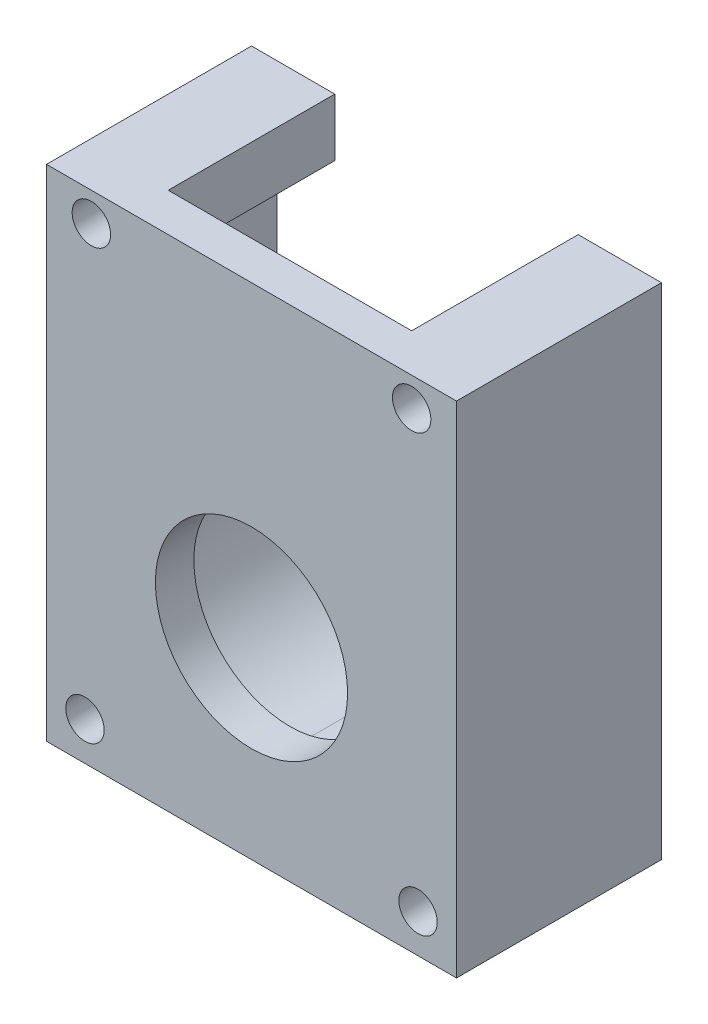
SolidWorks part; units mm, degrees
material "6063-O"
ref_plane "Front" through (0, 0, 0) normal (0, 0, 1) x (1, 0, 0)
ref_plane "Top" through (0, 0, 0) normal (0, 1, 0) x (1, 0, 0)
ref_plane "Right" through (0, 0, 0) normal (1, 0, 0) x (0, 0, -1)
sketch "Sketch1" plane through (0, 0, 0) normal (0, 0, 1) x (1, 0, 0)
  line L0 (-16, 0) -> (-16, 24)
  line L1 (-16, 24) -> (16, 24)
  line L2 (16, 24) -> (16, 0)
  line L3 (-14, 0) -> (-14, 24)
  line L4 (14, 0) -> (14, 24)
  line L5 (-16, 0) -> (-16, -15)
  line L6 (-16, -15) -> (16, -15)
  line L7 (16, -15) -> (16, 0)
  line L8 (14, -13) -> (14, 0)
  line L9 (14, 22) -> (14, 0)
  line L10 (-14, 22) -> (14, 22)
  line L11 (-14, 0) -> (-14, 22)
  line L12 (-14, 0) -> (-14, -13)
  line L13 (-14, -13) -> (14, -13)
  circle A0 centre (0, 0) radius 12.7
  circle A1 centre (0, 0) radius 14
  circle A2 centre (0, 0) radius 16
  dimension "D1" = 25.4
  dimension "D2" = 28
  dimension "D3" = 32
  dimension "D4" = 24
  dimension "D6" = 13
  dimension "D5" = 2
extrude "Boss-Extrude1" add sketch "Sketch1" along normal blind 19 contours A2 L11 L3 L1 L0 | L3 A2 L12 | A2 L5 L6 L13 L12 | L13 A2 L6 A1 | L13 A1 | A2 L6 L7 L8 L13 | A2 L4 L8 | A2 L2 L1 L4 L9
sketch "Sketch2" plane through (0, 0, 19) normal (0, 0, 1) x (1, 0, 0)
  line L1 (-14, 24) -> (-9.5, 24)
  line L2 (-14, 24) -> (-14, 19.5)
  line L3 (-14, 19.5) -> (-9.5, 19.5)
  line L4 (-9.5, 24) -> (-9.5, 19.5)
  line L7 (14, 24) -> (9.5, 24)
  line L8 (14, 24) -> (14, 19.5)
  line L9 (14, 19.5) -> (9.5, 19.5)
  line L10 (9.5, 24) -> (9.5, 19.5)
  dimension "D1" = 4.5
  dimension "4.5" = 4.5
extrude "Boss-Extrude2" add sketch "Sketch2" against normal blind 19
fillet "Fillet1" radius 10 1 edges at (-14, -13, 9.5)
fillet "Fillet2" radius 10 1 edges at (14, -13, 9.5)
fillet "Fillet3" radius 1 2 edges at (-14, 19.5, 9.5) (14, 19.5, 9.5)
sketch "Sketch3" plane through (0, 0, 19) normal (0, 0, 1) x (1, 0, 0)
  line L0 (-16, -15) -> (-16, 24) construction
  line L1 (-16, 24) -> (-9.5, 24) construction
  line L2 (-16, -15) -> (16, -15) construction
  line L3 (0, 25.8938) -> (0, -21.0154) construction
  circle A0 centre (-12.5, 21.75) radius 1.5
  circle A1 centre (-13, -12) radius 1.5
  circle A2 centre (12.5, 21.75) radius 1.5
  circle A3 centre (13, -12) radius 1.5
  dimension "D1" = 3
  dimension "D3" = 3
  dimension "D5" = 3
  dimension "D2" = 3.5
  dimension "22" = 2.25
  dimension "D4" = 3
extrude "Cut-Extrude1" cut sketch "Sketch3" against normal blind 19
sketch "Sketch4" plane through (0, 24, 0) normal (0, 1, 0) x (1, 0, 0)
  line L0 (16, -19) -> (16, 0) construction
  line L1 (-16, -19) -> (16, -19)
  line L2 (-16, -19) -> (-16, -16)
  line L3 (-16, -16) -> (16, -16)
  line L4 (16, -19) -> (16, -16)
  line L5 (-16, 0) -> (-9.5, 0) construction
  dimension "D1" = 16
extrude "Cut-Extrude2" cut sketch "Sketch4" against normal through all
sketch "Sketch5" plane through (0, 0, 16) normal (0, 0, 1) x (1, 0, 0)
  line L1 (-16, 24) -> (16, 24)
  line L2 (-16, 24) -> (-16, -15)
  line L3 (-16, -15) -> (16, -15)
  line L4 (16, 24) -> (16, -15)
  circle A25 centre (-12.5, 21.75) radius 1.5
  circle A26 centre (-12.5, 21.75) radius 1.5
  circle A28 centre (12.5, 21.75) radius 1.5
  circle A29 centre (12.5, 21.75) radius 1.5
  circle A31 centre (-13, -12) radius 1.5
  circle A32 centre (-13, -12) radius 1.5
  circle A34 centre (13, -12) radius 1.5
  circle A35 centre (13, -12) radius 1.5
  dimension "D1" = 0
  dimension "D2" = 0
  dimension "D3" = 0
  dimension "D4" = 0
extrude "Boss-Extrude3" add sketch "Sketch5" against normal blind 3
sketch "Sketch6" plane through (0, 0, 16) normal (0, 0, 1) x (1, 0, 0)
  circle A0 centre (0, 0) radius 7.5
  dimension "D1" = 15
extrude "Cut-Extrude3" cut sketch "Sketch6" against normal through all
